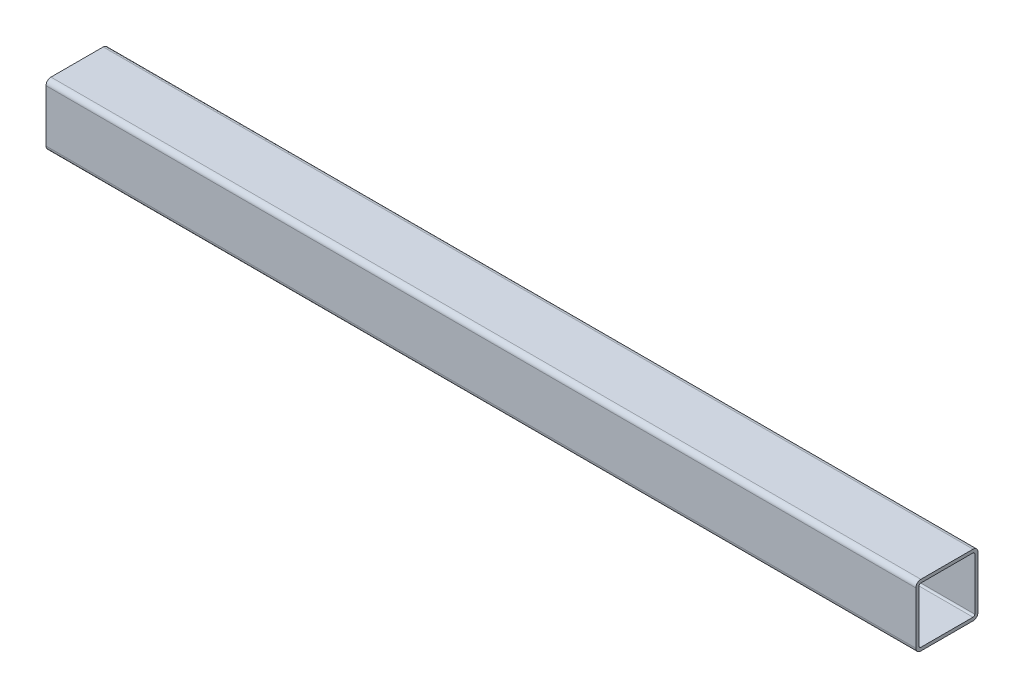
SolidWorks part; units mm, degrees
material "Plain Carbon Steel"
ref_plane "Front Plane" through (0, 0, 0) normal (0, 0, 1) x (1, 0, 0)
ref_plane "Top Plane" through (0, 0, 0) normal (0, 1, 0) x (1, 0, 0)
ref_plane "Right Plane" through (0, 0, 0) normal (1, 0, 0) x (0, 0, -1)
sketch "Sketch1" plane through (0, 0, 0) normal (1, 0, 0) x (0, 0, -1)
  line L0 (0, 2.54) -> (0, 29.21)
  line L1 (-2.54, 31.75) -> (-29.21, 31.75)
  line L2 (-31.75, 29.21) -> (-31.75, 2.54)
  line L3 (-29.21, 0) -> (-2.54, 0)
  line L4 (-1.651, 2.54) -> (-1.651, 29.21)
  line L5 (-2.54, 30.099) -> (-29.21, 30.099)
  line L6 (-30.099, 29.21) -> (-30.099, 2.54)
  line L7 (-29.21, 1.651) -> (-2.54, 1.651)
  arc A0 (-31.75, 2.54) -> (-29.21, 0) centre (-29.21, 2.54) ccw
  arc A1 (0, 2.54) -> (-2.54, 0) centre (-2.54, 2.54) cw
  arc A2 (0, 29.21) -> (-2.54, 31.75) centre (-2.54, 29.21) ccw
  arc A3 (-31.75, 29.21) -> (-29.21, 31.75) centre (-29.21, 29.21) cw
  arc A4 (-1.651, 29.21) -> (-2.54, 30.099) centre (-2.54, 29.21) ccw
  arc A5 (-30.099, 29.21) -> (-29.21, 30.099) centre (-29.21, 29.21) cw
  arc A6 (-30.099, 2.54) -> (-29.21, 1.651) centre (-29.21, 2.54) ccw
  arc A7 (-1.651, 2.54) -> (-2.54, 1.651) centre (-2.54, 2.54) cw
  point P12 (0, 0)
  point P15 (0, 31.75)
  point P18 (-31.75, 31.75)
  dimension "D3" = 2.54
  dimension "D1" = 31.75
  dimension "D2" = 31.75
  dimension "D4" = 1.651
extrude "Boss-Extrude1" add sketch "Sketch1" along normal blind 177.8
scale "Scale1" scale about centroid uniform scaling no x scale factor 1 y scale factor 0.4 z scale factor 0.4
